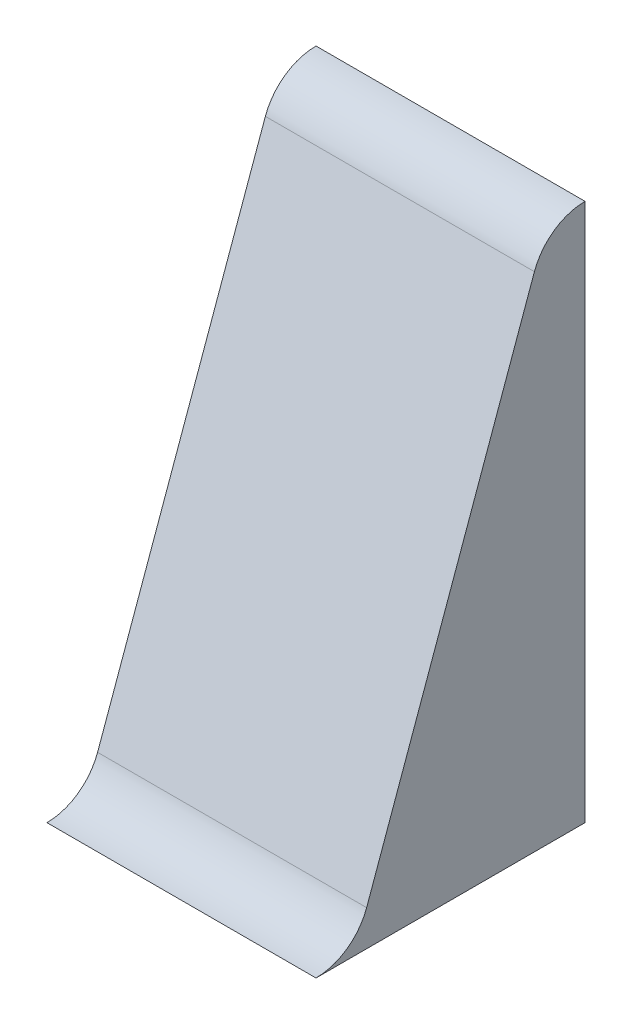
SolidWorks part; units mm, degrees
ref_plane "Ebene vorne" through (0, 0, 0) normal (0, 0, 1) x (1, 0, 0)
ref_plane "Ebene oben" through (0, 0, 0) normal (0, 1, 0) x (1, 0, 0)
ref_plane "Ebene rechts" through (0, 0, 0) normal (1, 0, 0) x (0, 0, -1)
sketch "Skizze1" plane through (0, 0, 0) normal (1, 0, 0) x (0, 0, -1)
  line L0 (0, 0) -> (1000, 0)
  line L1 (1000, 0) -> (1000, 2000)
  line L2 (1000, 2000) -> (3265.0444, 2000) construction
  line L3 (811.7835, 1867.6353) -> (188.2165, 132.3647)
  line L4 (0, 0) -> (-111.0896, 0) construction
  arc A0 (1000, 2000) -> (811.7835, 1867.6353) centre (1000, 1800) ccw
  arc A1 (0, 0) -> (188.2165, 132.3647) centre (0, 200) ccw
  dimension "D3" = 200
  dimension "D4" = 200
  dimension "D1" = 1000
  dimension "D2" = 2000
extrude "Aufsatz-Linear austragen1" add sketch "Skizze1" along normal blind 1000
